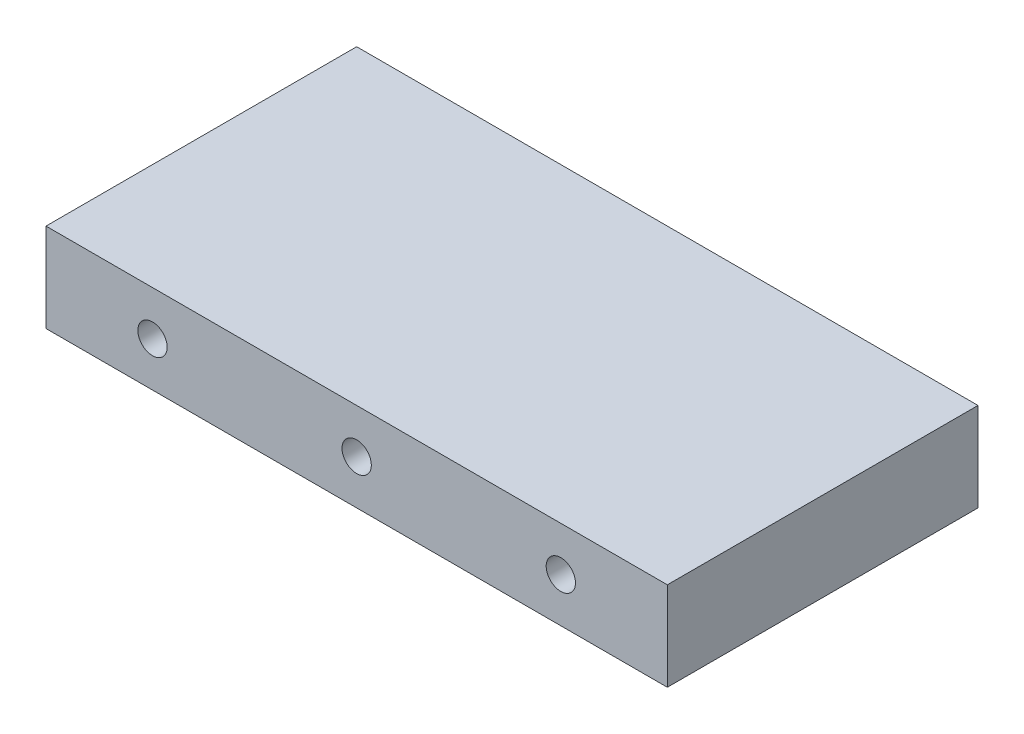
SolidWorks part; units mm, degrees
material "7079 Alloy"
ref_plane "Front Plane" through (0, 0, 0) normal (0, 0, 1) x (1, 0, 0)
ref_plane "Top Plane" through (0, 0, 0) normal (0, 1, 0) x (1, 0, 0)
ref_plane "Right Plane" through (0, 0, 0) normal (1, 0, 0) x (0, 0, -1)
sketch "Sketch1" plane through (0, 0, 0) normal (0, 1, 0) x (1, 0, 0)
  line L1 (35, -17.5) -> (-35, -17.5)
  line L2 (35, -17.5) -> (35, 17.5)
  line L3 (35, 17.5) -> (-35, 17.5)
  line L4 (-35, -17.5) -> (-35, 17.5)
  line L5 (35, -17.5) -> (-35, 17.5) construction
  line L6 (35, 17.5) -> (-35, -17.5) construction
  point P0 (0, 0)
  dimension "D1" = 70
  dimension "D2" = 35
extrude "Boss-Extrude1" add sketch "Sketch1" along normal blind 10
sketch "Sketch2" plane through (0, 0, 17.5) normal (0, 0, 1) x (1, 0, 0)
  line L0 (35, 5) -> (-35, 5) construction
  line L1 (35, 10) -> (35, 0) construction
  line L2 (-35, 10) -> (-35, 0) construction
  line L3 (0, 0) -> (0, 10) construction
  line L4 (-35, 0) -> (35, 0) construction
  line L5 (-35, 10) -> (35, 10) construction
  circle A0 centre (0, 5) radius 1.65
  circle A1 centre (-23, 5) radius 1.65
  circle A2 centre (23, 5) radius 1.65
  dimension "D1" = 3.3
  dimension "D2" = 23
extrude "Cut-Extrude1" cut sketch "Sketch2" against normal blind 10
ref_plane "Plane1" through (0, 0, 0) normal (0, 0, 1) x (1, 0, 0)
mirror "Mirror1" about plane through (0, 0, 0) normal (0, 0, 1) of "Cut-Extrude1"
